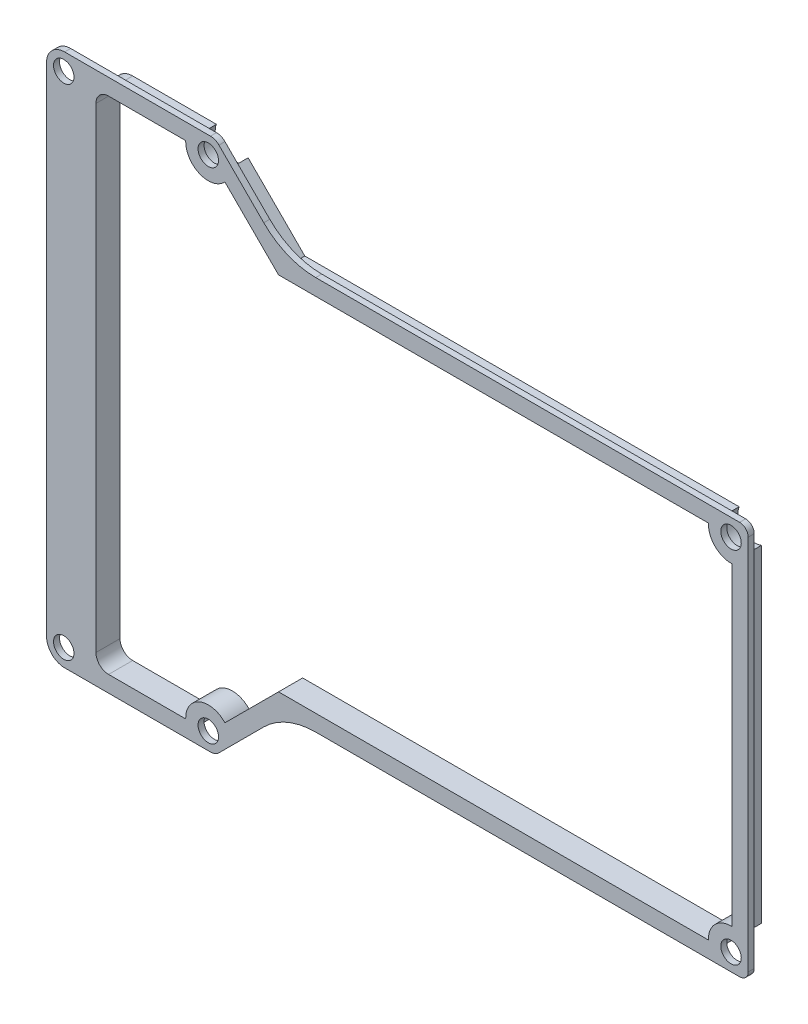
SolidWorks part; units mm, degrees
ref_plane "Front Plane" through (0, 0, 0) normal (0, 0, 1) x (1, 0, 0)
ref_plane "Top Plane" through (0, 0, 0) normal (0, 1, 0) x (1, 0, 0)
ref_plane "Right Plane" through (0, 0, 0) normal (1, 0, 0) x (0, 0, -1)
sketch "Sketch2" plane through (0, 0, 0) normal (0, 0, 1) x (1, 0, 0)
  line L8 (28.7801, -21.4985) -> (21.333, -14.0514)
  line L9 (107.834, -25.0706) -> (37.404, -25.0706)
  line L10 (109.259, -89.0386) -> (109.259, -26.4956)
  line L11 (37.409, -90.4636) -> (107.834, -90.4636)
  line L12 (21.333, -101.4878) -> (28.7851, -94.0357)
  line L13 (-4.3, -102.0736) -> (19.9188, -102.0736)
  line L14 (-7.3, -16.4656) -> (-7.3, -99.0736)
  line L15 (19.9188, -13.4656) -> (-4.3, -13.4656)
  line L16 (15.8154, -99.3696) -> (3, -99.3696)
  line L17 (31.2372, -87.7596) -> (22.3225, -96.6743)
  line L18 (102.656, -87.7596) -> (31.2372, -87.7596)
  line L19 (106.555, -83.8606) -> (106.555, -31.6736)
  line L20 (31.2322, -27.7746) -> (102.656, -27.7746)
  line L21 (22.3225, -18.8649) -> (31.2322, -27.7746)
  line L22 (0.9, -97.2696) -> (0.9, -18.2696)
  line L23 (3, -16.1696) -> (15.8154, -16.1696)
  circle A6 centre (106.406, -27.9236) radius 1.7
  circle A7 centre (19.5655, -16.3186) radius 1.7
  arc A8 (21.333, -14.0514) -> (19.9188, -13.4656) centre (19.9188, -15.4656) ccw
  arc A9 (28.7801, -21.4985) -> (37.404, -25.0706) centre (37.404, -12.8746) ccw
  arc A10 (109.259, -26.4956) -> (107.834, -25.0706) centre (107.834, -26.4956) ccw
  arc A11 (107.834, -90.4636) -> (109.259, -89.0386) centre (107.834, -89.0386) ccw
  arc A12 (37.409, -90.4636) -> (28.7851, -94.0357) centre (37.409, -102.6596) ccw
  arc A13 (19.9188, -102.0736) -> (21.333, -101.4878) centre (19.9188, -100.0736) ccw
  arc A14 (-7.3, -99.0736) -> (-4.3, -102.0736) centre (-4.3, -99.0736) ccw
  arc A15 (-4.3, -13.4656) -> (-7.3, -16.4656) centre (-4.3, -16.4656) ccw
  circle A16 centre (-4.447, -16.3186) radius 1.7
  circle A17 centre (-4.447, -99.2206) radius 1.7
  circle A18 centre (19.5655, -99.2206) radius 1.7
  circle A19 centre (106.406, -87.6106) radius 1.7
  arc A26 (0.9, -97.2696) -> (3, -99.3696) centre (3, -97.2696) ccw
  arc A27 (22.3225, -96.6743) -> (15.8154, -99.3696) centre (19.5655, -99.2206) ccw
  arc A28 (106.555, -83.8606) -> (102.656, -87.7596) centre (106.406, -87.6106) ccw
  arc A29 (102.656, -27.7746) -> (106.555, -31.6736) centre (106.406, -27.9236) ccw
  arc A30 (15.8154, -16.1696) -> (22.3225, -18.8649) centre (19.5655, -16.3186) ccw
  arc A31 (3, -16.1696) -> (0.9, -18.2696) centre (3, -18.2696) ccw
extrude "Boss-Extrude1" add sketch "Sketch2" along normal blind 1
sketch "Sketch3" plane through (0, 0, 0) normal (0, 0, 1) x (1, 0, 0)
  line L16 (31.605, -26.8746) -> (103.7528, -26.8746)
  line L17 (102.656, -27.7746) -> (31.2322, -27.7746)
  line L18 (107.455, -84.9574) -> (107.455, -30.5767)
  line L19 (106.555, -83.8606) -> (106.555, -31.6736)
  line L20 (103.7528, -88.6596) -> (31.61, -88.6596)
  line L21 (31.2372, -87.7596) -> (102.656, -87.7596)
  line L22 (31.61, -88.6596) -> (22.1833, -98.0863)
  line L23 (22.3225, -96.6743) -> (31.2372, -87.7596)
  line L24 (3, -99.3696) -> (15.8154, -99.3696)
  line L25 (16.9123, -100.2696) -> (3, -100.2696)
  line L26 (0, -97.2696) -> (0, -18.2696)
  line L27 (0.9, -18.2696) -> (0.9, -97.2696)
  line L28 (15.8154, -16.1696) -> (3, -16.1696)
  line L29 (31.2322, -27.7746) -> (22.3225, -18.8649)
  line L30 (22.1833, -17.4529) -> (31.605, -26.8746)
  line L31 (3, -15.2696) -> (16.9123, -15.2696)
  arc A12 (102.656, -27.7746) -> (106.555, -31.6736) centre (106.406, -27.9236) ccw
  arc A13 (103.7528, -26.8746) -> (107.455, -30.5767) centre (106.406, -27.9236) ccw
  arc A14 (106.555, -83.8606) -> (102.656, -87.7596) centre (106.406, -87.6106) ccw
  arc A15 (107.455, -84.9574) -> (103.7528, -88.6596) centre (106.406, -87.6106) ccw
  arc A16 (22.1833, -98.0863) -> (16.9123, -100.2696) centre (19.5655, -99.2206) ccw
  arc A17 (22.3225, -96.6743) -> (15.8154, -99.3696) centre (19.5655, -99.2206) ccw
  arc A18 (0, -97.2696) -> (3, -100.2696) centre (3, -97.2696) ccw
  arc A19 (0.9, -97.2696) -> (3, -99.3696) centre (3, -97.2696) ccw
  arc A20 (3, -16.1696) -> (0.9, -18.2696) centre (3, -18.2696) ccw
  arc A21 (3, -15.2696) -> (0, -18.2696) centre (3, -18.2696) ccw
  arc A22 (15.8154, -16.1696) -> (22.3225, -18.8649) centre (19.5655, -16.3186) ccw
  arc A23 (16.9123, -15.2696) -> (22.1833, -17.4529) centre (19.5655, -16.3186) ccw
extrude "Boss-Extrude2" add sketch "Sketch3" against normal blind 3
